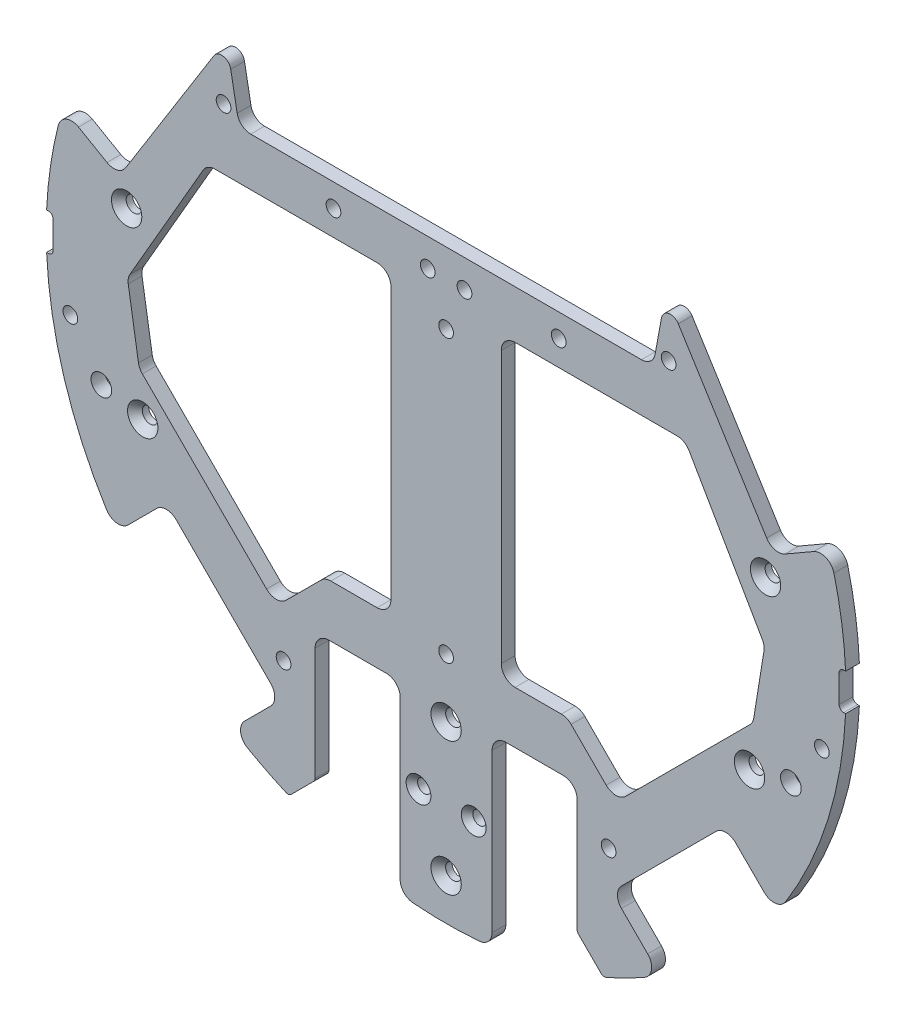
SolidWorks part; units mm, degrees
material "Thornel Mat VMA"
ref_plane "前视基准面" through (0, 0, 0) normal (0, 0, 1) x (1, 0, 0)
ref_plane "上视基准面" through (0, 0, 0) normal (0, 1, 0) x (1, 0, 0)
ref_plane "右视基准面" through (0, 0, 0) normal (1, 0, 0) x (0, 0, -1)
sketch "草图1" plane through (0, 0, 0) normal (0, 0, 1) x (1, 0, 0)
  line L0 (-89, 0) -> (89, 0) construction
  line L1 (0, 89) -> (0, -88.915) construction
  line L2 (0, 0) -> (-59.3634, 37.0943) construction
  line L3 (0, 0) -> (-48.0833, -48.0833) construction
  line L4 (-45, 40.4846) -> (-47.7909, 55.6142)
  line L5 (-47.7909, 55.6142) -> (-71.2581, 18.0588)
  line L7 (-71.2581, 18.0588) -> (-85.1051, 26.0408)
  line L10 (-60.8396, -38.1553) -> (-73.2441, -50.5599)
  line L11 (-36.0301, -62.9648) -> (-48.0073, -74.942)
  line L12 (-60.8396, -38.1553) -> (-36.0301, -62.9648)
  line L13 (-48.0833, -48.0833) -> (-49.4975, -49.4975) construction
  line L14 (-45, 40.4846) -> (0, 40.4846)
  line L16 (0, 40.4846) -> (0, -88.915)
  line L17 (-10, -46.3509) -> (-10, -88.3509)
  line L18 (-28.5, -84.3134) -> (-28.5, -46.3509)
  line L19 (-28.5, -46.3509) -> (-10, -46.3509)
  arc A0 (-85.1051, 26.0408) -> (-73.2441, -50.5599) centre (0, 0) ccw
  arc A1 (-48.0073, -74.942) -> (-28.5, -84.3134) centre (0, 0) ccw
  arc A2 (0, -88.915) -> (-10, -88.3509) centre (0, 0) cw
  dimension "D10" = 89
  dimension "D1" = 45
  dimension "D2" = 32
  dimension "D3" = 68
  dimension "D4" = 129.3996
  dimension "D5" = 45
  dimension "D6" = 2
  dimension "D7" = 44.2844
  dimension "D8" = 70
  dimension "D9" = 42
  dimension "D11" = 18.5
  dimension "D12" = 10
  dimension "D13" = 16.0402
  dimension "D14" = 19.0457
extrude "凸台-拉伸1" add sketch "草图1" along normal blind 3
sketch "草图2" plane through (0, 0, 3) normal (0, 0, 1) x (1, 0, 0)
  line L0 (0, 0) -> (-12, 0) construction
  line L1 (-12, 0) -> (-12, 30)
  line L2 (-12, 30) -> (-52, 30)
  line L3 (-52, 30) -> (-69.3205, 0)
  line L4 (-69.3205, 0) -> (-66.7695, -15.7953)
  line L5 (-66.7695, -15.7953) -> (-36.9392, -45.6255)
  line L6 (-12, 0) -> (-12, -35)
  line L7 (-12, -35) -> (-26.3137, -35)
  line L8 (-26.3137, -35) -> (-36.9392, -45.6255)
extrude "切除-拉伸1" cut sketch "草图2" against normal up to next
fillet "圆角1" radius 3 4 edges at (-45, 40.4846, 1.5) (-71.2581, 18.0588, 1.5) (-60.8396, -38.1553, 1.5) (-36.0301, -62.9648, 1.5)
fillet "圆角3" radius 3 7 edges at (-69.3205, 0, 1.5) (-66.7695, -15.7953, 1.5) (-36.9392, -45.6255, 1.5) (-12, 30, 1.5) (-52, 30, 1.5) (-12, -35, 1.5) (-26.3137, -35, 1.5)
mirror "镜向2" about plane through (0, 40.4846, 3) normal (-1, 0, 0) of bodies 107
sketch "草图3" plane through (0, 0, 3) normal (0, 0, 1) x (1, 0, 0)
  line L0 (-81.7399, -13.2015) -> (0, 0) construction
  line L1 (-89, 0) -> (89, 0) construction
  line L4 (0, 0) -> (0, 25) construction
  line L5 (0, 40.4846) -> (0, -88.915) construction
  line L7 (0, -36.25) -> (0, 0) construction
  circle A0 centre (-81.7399, -13.2015) radius 1.6
  circle A1 centre (0, -36.25) radius 1.6
  circle A2 centre (0, 25) radius 1.6
  circle A3 centre (81.7399, -13.2015) radius 1.6
  dimension "D3" = 36.25
  dimension "D1" = 9.174
  dimension "D2" = 82.7991
  dimension "D4" = 25
extrude "切除-拉伸2" cut sketch "草图3" against normal up to next
fillet "圆角4" radius 2 2 edges at (-47.7909, 55.6142, 1.5) (47.7909, 55.6142, 1.5)
sketch "草图5" plane through (0, 0, 3) normal (0, 0, 1) x (1, 0, 0)
  line L1 (0, 40.4846) -> (0, 34.3996) construction
  line L3 (0, 34.3996) -> (-4, 34.3996) construction
  line L4 (0, 34.3996) -> (4, 34.3996) construction
  circle A0 centre (-4, 34.3996) radius 1.6
  circle A1 centre (4, 34.3996) radius 1.6
extrude "切除-拉伸4" cut sketch "草图5" against normal up to next
sketch "草图6" plane through (0, 0, 3) normal (0, 0, 1) x (1, 0, 0)
  line L0 (0, 0) -> (-69.5, 13) construction
  line L1 (0, 0) -> (-66, -25) construction
  line L2 (0, 0) -> (-75, -23) construction
  line L3 (0, 0) -> (0, -27.0074) construction
  line L4 (0, 40.4846) -> (0, -88.915) construction
  circle A0 centre (-69.5, 13) radius 3.3 construction
  circle A1 centre (-69.5, 13) radius 1.7 construction
  circle A2 centre (-66, -25) radius 1.7 construction
  circle A3 centre (-75, -23) radius 2.25
  circle A4 centre (-66, -25) radius 3.3 construction
  circle A5 centre (66, -25) radius 3.3 construction
  circle A6 centre (66, -25) radius 1.7 construction
  circle A7 centre (75, -23) radius 2.25
  circle A8 centre (69.5, 13) radius 3.3 construction
  circle A9 centre (69.5, 13) radius 1.7 construction
extrude "切除-拉伸5" cut sketch "草图6" against normal up to next
sketch "草图7" plane through (0, 0, 3) normal (0, 0, 1) x (1, 0, 0)
  line L0 (0, 0) -> (0, -33.6173) construction
  line L1 (0, 40.4846) -> (0, -88.915) construction
  circle A0 centre (-69.5, 13) radius 1.7
  circle A1 centre (-69.5, 13) radius 3.3
  circle A2 centre (-66, -25) radius 1.7
  circle A3 centre (-66, -25) radius 3.3
  circle A4 centre (66, -25) radius 3.3
  circle A5 centre (66, -25) radius 1.7
  circle A6 centre (69.5, 13) radius 3.3
  circle A7 centre (69.5, 13) radius 1.7
hole_wizard "打孔尺寸(%根据十字)槽沉头木螺钉的类型1" positions "3D草图1" profile "草图8" countersink size "M3" standard "GB"
sketch3d "3D草图1"
  point P0 (-69.5, 13, 3)
  point P3 (-66, -25, 3)
  point P6 (69.5, 13, 3)
  point P9 (66, -25, 3)
sketch "草图8" plane through (-69.5, 13, 3) normal (1, 0, 0) x (0, -1, 0)
  line L0 (0, 0) -> (0, 4.0215)
  line L1 (0, 4.0215) -> (1.7, 3)
  line L2 (1.7, 3) -> (1.7, 1.6)
  line L3 (1.7, 1.6) -> (3.3, 0)
  line L5 (3.3, 0) -> (0, 0)
  line L6 (-1.7, 1.6) -> (-3.3, 0) construction
  line L10 (0, 4.0215) -> (-1.7, 3) construction
  line L11 (0, -6.35) -> (0, 107.95) construction
  dimension "孔直径" = 3.4
  dimension "孔深度" = 3
  dimension "近端锥形沉头孔直径" = 6.6
  dimension "近端锥形沉头孔角度" = 90
  dimension "导头角度" = 118
sketch "草图9" plane through (0, 0, 3) normal (0, 0, 1) x (1, 0, 0)
  line L0 (-60.8396, -38.1553) -> (-36.0301, -62.9648) construction
  line L1 (-52.3338, 39.7769) -> (-51.0617, 38.982) construction
  line L2 (-51.0617, 38.982) -> (-48.4121, 43.2222) construction
  line L3 (0, 0) -> (0, 40.4846) construction
  line L4 (-54.0937, -38.5373) -> (-39.9515, -52.6795) construction
  line L5 (-39.9515, -52.6795) -> (-38.8909, -51.6188) construction
  line L6 (-38.8909, -51.6188) -> (-35.3553, -55.1543) construction
  line L7 (0, 0) -> (-59.3634, 37.0943) construction
  line L8 (-52.3338, 39.7769) -> (-55.5133, 34.6886) construction
  circle A0 centre (-48.4121, 43.2222) radius 1.6
  circle A1 centre (-35.3553, -55.1543) radius 1.6
  circle A2 centre (48.4121, 43.2222) radius 1.6
  circle A3 centre (35.3553, -55.1543) radius 1.6
  point P14 (-48.4349, -50.5601)
  dimension "D1" = 6
  dimension "D2" = 1.5
  dimension "D3" = 5
  dimension "D4" = 20
  dimension "D5" = 1.5
  dimension "D6" = 5
  dimension "D7" = 4.5
extrude "切除-拉伸6" cut sketch "草图9" against normal up to next
sketch "草图10" plane through (0, 0, 3) normal (0, 0, 1) x (1, 0, 0)
  circle A0 centre (0, 0) radius 87
  circle A1 centre (0, 0) radius 107.1539
extrude "切除-拉伸7" cut sketch "草图10" against normal blind 10
fillet "圆角5" radius 3 6 edges at (83.3261, 25.0153, 1.5) (71.8058, -49.1215, 1.5) (46.5587, -73.4934, 1.5) (-46.5587, -73.4934, 1.5) (-71.8058, -49.1215, 1.5) (-83.3261, 25.0153, 1.5)
sketch "草图12" plane through (0, 0, 3) normal (0, 0, 1) x (1, 0, 0)
  line L0 (-87, 0) -> (-85.5, 0) construction
  line L1 (-89, 0) -> (89, 0) construction
  line L2 (-85.5, 4) -> (-85.5, -4)
  line L3 (0, 0) -> (0, -20.5829) construction
  line L4 (-85.5, -4) -> (-87.9922, -4)
  line L5 (-87.9922, -4) -> (-87.9922, 4)
  line L6 (-87.9922, 4) -> (-85.5, 4)
  line L7 (0, 40.4846) -> (0, -88.915) construction
  line L14 (87, 0) -> (85.5, 0) construction
  line L15 (85.5, 4) -> (87.9922, 4)
  line L16 (87.9922, -4) -> (85.5, -4)
  line L22 (87.9922, -4) -> (87.9922, 4)
  line L24 (85.5, 4) -> (85.5, -4)
  arc A0 (-84.3747, 21.2113) -> (-73.8614, -45.9728) centre (0, 0) ccw construction
  dimension "D1" = 1.5
extrude "切除-拉伸8" cut sketch "草图12" against normal blind 10
fillet "圆角6" radius 1 4 edges at (85.5, -4, 1.5) (85.5, 4, 1.5) (-85.5, -4, 1.5) (-85.5, 4, 1.5)
fillet "圆角7" radius 3 8 edges at (28.5, -82.1995, 1.5) (28.5, -46.3509, 1.5) (10, -46.3509, 1.5) (10, -86.4234, 1.5) (-10, -46.3509, 1.5) (-28.5, -46.3509, 1.5) (-28.5, -82.1995, 1.5) (-10, -86.4234, 1.5)
sketch "草图13" plane through (0, 0, 3) normal (0, 0, 1) x (1, 0, 0)
  line L0 (66, -25) -> (0, -25) construction
  line L1 (0, -25) -> (0, -49) construction
  line L2 (0, -25) -> (0, -78) construction
  line L3 (0, -77.8803) -> (-6, -64.6969) construction
  line L4 (-6, -64.6969) -> (6, -64.6969) construction
  line L5 (6, -64.6969) -> (0, -77.8803) construction
  point P5 (0, -49)
  point P11 (6, -64.6969)
  point P12 (-6, -64.6969)
  dimension "D2" = 24
  dimension "D4" = 53
hole_wizard "打孔尺寸(%根据十字)槽沉头木螺钉的类型2" positions "3D草图3" profile "草图15" countersink size "M3" standard "GB"
sketch3d "3D草图3"
  point P0 (0, -49, 3)
  point P3 (0, -78, 3)
sketch "草图15" plane through (0, -49, 3) normal (1, 0, 0) x (0, -1, 0)
  line L0 (0, 0) -> (0, 4.0215)
  line L1 (0, 4.0215) -> (1.7, 3)
  line L2 (1.7, 3) -> (1.7, 1.6)
  line L3 (1.7, 1.6) -> (3.3, 0)
  line L5 (3.3, 0) -> (0, 0)
  line L6 (-1.7, 1.6) -> (-3.3, 0) construction
  line L10 (0, 4.0215) -> (-1.7, 3) construction
  line L11 (0, -6.35) -> (0, 107.95) construction
  dimension "孔直径" = 3.4
  dimension "孔深度" = 3
  dimension "近端锥形沉头孔直径" = 6.6
  dimension "近端锥形沉头孔角度" = 90
  dimension "导头角度" = 118
hole_wizard "打孔尺寸(%根据十字)槽沉头木螺钉的类型3" positions "3D草图4" profile "草图16" countersink size "M2.5" standard "GB"
sketch3d "3D草图4"
  point P0 (-6, -64.6969, 3)
  point P3 (6, -64.6969, 3)
sketch "草图16" plane through (-6, -64.6969, 3) normal (1, 0, 0) x (0, -1, 0)
  line L0 (0, 0) -> (0, 3.8712)
  line L1 (0, 3.8712) -> (1.45, 3)
  line L2 (1.45, 3) -> (1.45, 1.25)
  line L3 (1.45, 1.25) -> (2.7, 0)
  line L5 (2.7, 0) -> (0, 0)
  line L6 (-1.45, 1.25) -> (-2.7, 0) construction
  line L10 (0, 3.8712) -> (-1.45, 3) construction
  line L11 (0, -6.35) -> (0, 107.95) construction
  dimension "孔直径" = 2.9
  dimension "孔深度" = 3
  dimension "近端锥形沉头孔直径" = 5.4
  dimension "近端锥形沉头孔角度" = 90
  dimension "导头角度" = 118
sketch "草图17" plane through (0, 0, 3) normal (0, 0, 1) x (1, 0, 0)
  line L0 (-28.5, -84.3134) -> (-28.5, -74.3134)
  line L2 (-28.5, -84.3134) -> (-28.5, -46.3509) construction
  line L3 (-28.5, -74.3134) -> (-35.7089, -81.5223)
  line L4 (-35.7089, -81.5223) -> (-28.5, -84.3134)
  line L5 (0, -38.148) -> (0, -99.5518) construction
  line L6 (0, 40.4846) -> (0, -88.915) construction
  line L7 (35.7089, -81.5223) -> (28.5, -84.3134)
  line L8 (28.5, -74.3134) -> (35.7089, -81.5223)
  line L9 (28.5, -84.3134) -> (28.5, -74.3134)
  arc A0 (-48.0073, -74.942) -> (-28.5, -84.3134) centre (0, 0) ccw construction
extrude "切除-拉伸10" cut sketch "草图17" against normal blind 10
fillet "圆角8" radius 1 4 edges at (28.5, -74.3134, 1.5) (34.1878, -80.0012, 1.5) (-28.5, -74.3134, 1.5) (-34.1878, -80.0012, 1.5)
sketch "Sketch1" plane through (0, 0, 3) normal (0, 0, 1) x (1, 0, 0)
  line L0 (0, 40.4846) -> (0, -88.915) construction
  line L1 (-45, 40.4846) -> (0, 40.4846) construction
  line L2 (42.5028, 40.4846) -> (-42.5028, 40.4846) construction
  circle A0 centre (24.5, 35.4846) radius 1.6
  circle A1 centre (-24.5, 35.4846) radius 1.6
  dimension "D1" = 3.2
  dimension "D2" = 3.2
  dimension "D3" = 24.5
  dimension "D4" = 24.5
  dimension "D5" = 5
  dimension "D6" = 5
extrude "Extrude1" cut sketch "Sketch1" against normal blind 10
